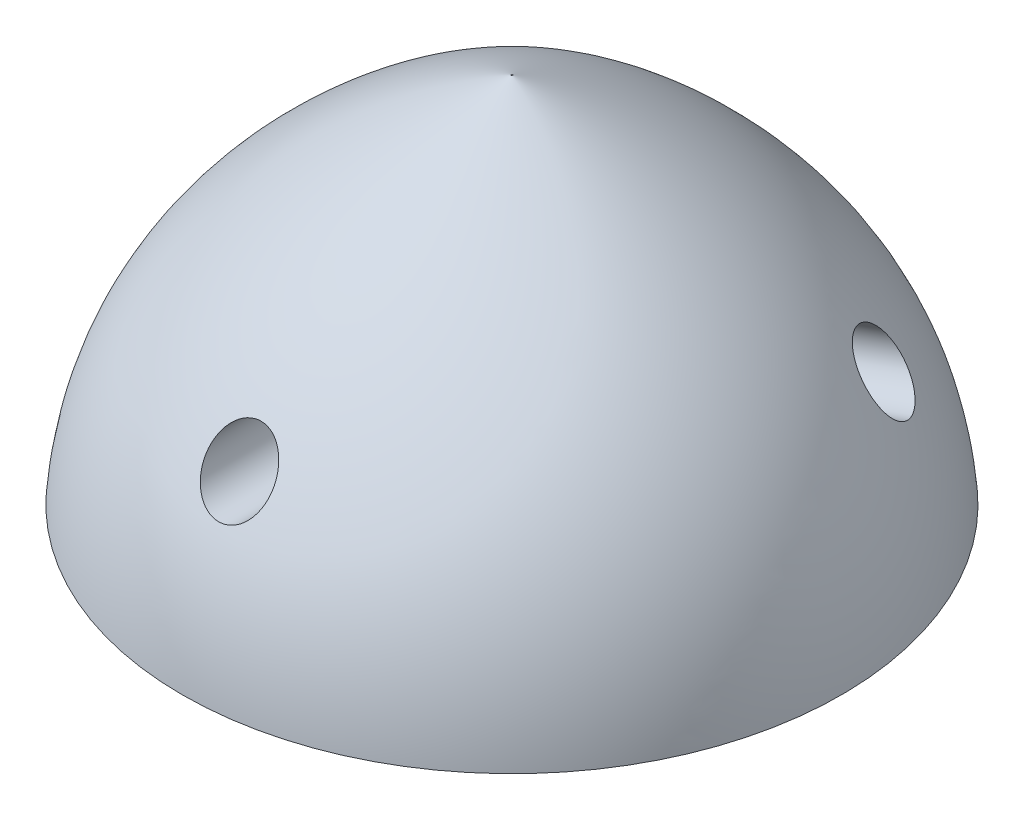
SolidWorks part; units mm, degrees
material "Stainless Steel (ferritic)"
ref_plane "Front Plane" through (0, 0, 0) normal (0, 0, 1) x (1, 0, 0)
ref_plane "Top Plane" through (0, 0, 0) normal (0, 1, 0) x (1, 0, 0)
ref_plane "Right Plane" through (0, 0, 0) normal (1, 0, 0) x (0, 0, -1)
sketch "Sketch1" plane through (0, 0, 0) normal (0, 0, 1) x (1, 0, 0)
  line L0 (0, 52.1873) -> (0, -51.7551) construction
  line L1 (-56.1851, 0) -> (71.7441, 0) construction
  line L2 (0, 0) -> (8000, 0)
  line L3 (0, 0) -> (0, 9000)
  line L4 (0, 9000) -> (13.1109, 9028.6336)
  spline S0 degree 2 poles (13.1109, 9028.6336) (7529.8526, 5849.0531) (8000, 0) knots 0 0 0 0.656149 0.656149 0.656149
  dimension "D1" = 8000
  dimension "D2" = 9000
revolve "Revolve1" add sketch "Sketch1" angle 360 about L0
ref_plane "Plane1" through (0, 0, 8000) normal (0, 0, 1) x (1, 0, 0)
sketch "Sketch2" plane through (0, 0, 8000) normal (0, 0, 1) x (1, 0, 0)
  line L0 (0, 10405.4191) -> (0, -1129.0964) construction
  line L1 (-9821.0503, 0) -> (10254.1125, 0) construction
  circle A0 centre (0, 4000) radius 800
  point P1 (0, 0)
  dimension "D1" = 4000
  dimension "D2" = 1600
extrude "Cut-Extrude1" cut sketch "Sketch2" against normal blind 5333.3333
pattern_circular "CirPattern1" count 3 over 360 about axis through (0, 0, 0) along (0, 1, 0) of "Cut-Extrude1"
